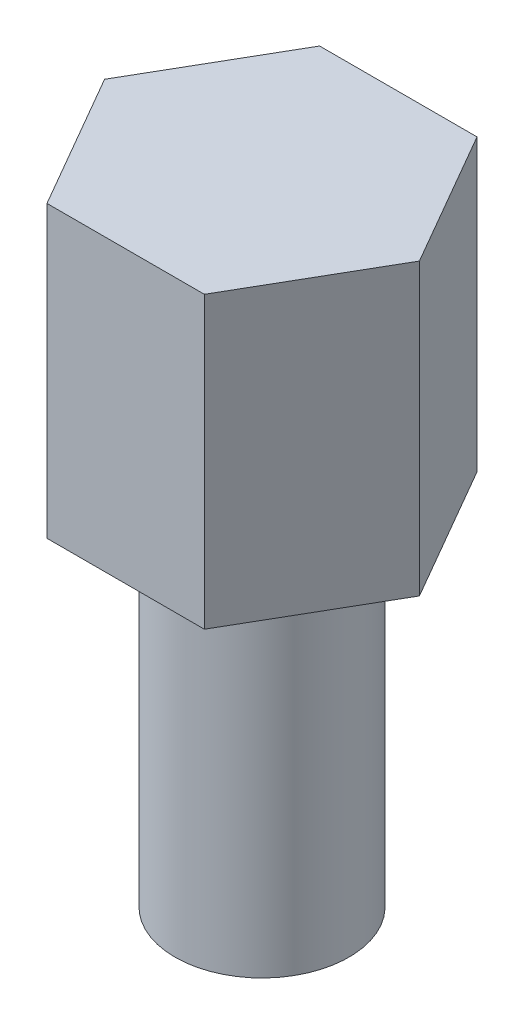
SolidWorks part; units mm, degrees
ref_plane "前视基准面" through (0, 0, 0) normal (0, 0, 1) x (1, 0, 0)
ref_plane "上视基准面" through (0, 0, 0) normal (0, 1, 0) x (1, 0, 0)
ref_plane "右视基准面" through (0, 0, 0) normal (1, 0, 0) x (0, 0, -1)
sketch "草图1" plane through (0, 0, 0) normal (0, 1, 0) x (1, 0, 0)
  line L1 (-1.3568, 2.35) -> (-2.7135, 0)
  line L2 (-2.7135, 0) -> (-1.3568, -2.35)
  line L3 (-1.3568, -2.35) -> (1.3568, -2.35)
  line L4 (1.3568, -2.35) -> (2.7135, 0)
  line L5 (2.7135, 0) -> (1.3568, 2.35)
  line L6 (1.3568, 2.35) -> (-1.3568, 2.35)
  circle A0 centre (0, 0) radius 2.35 construction
  dimension "D1" = 4.7
extrude "凸台-拉伸1" add sketch "草图1" along normal blind 5
sketch "草图2" plane through (0, 0, 0) normal (0, -1, 0) x (1, 0, 0)
  circle A0 centre (0, 0) radius 1.5
  dimension "D1" = 3
extrude "凸台-拉伸2" add sketch "草图2" along normal blind 6
